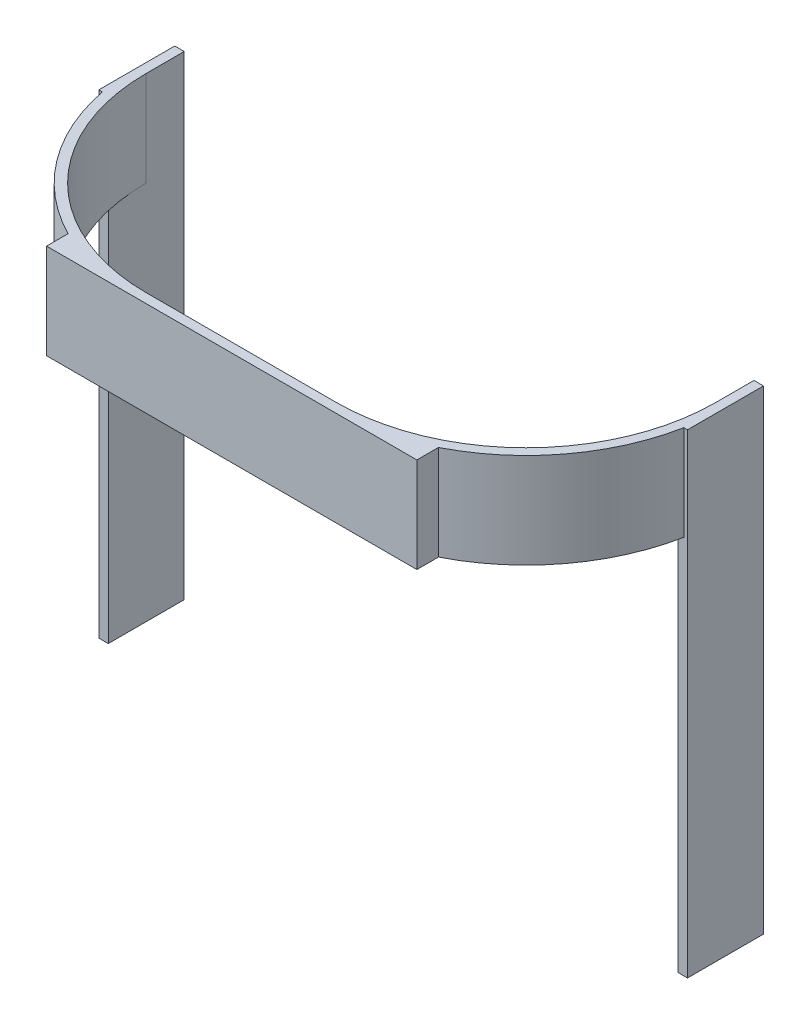
SolidWorks part; units mm, degrees
ref_plane "Front" through (0, 0, 0) normal (0, 0, 1) x (1, 0, 0)
ref_plane "Top" through (0, 0, 0) normal (0, 1, 0) x (1, 0, 0)
ref_plane "Right" through (0, 0, 0) normal (1, 0, 0) x (0, 0, -1)
sketch "草图2" plane through (0, 0, 0) normal (0, 1, 0) x (1, 0, 0)
  line L0 (-0.7345, 0) -> (19.6327, 0) construction
  line L2 (-40, -80) -> (40, -80)
  line L3 (-0.7345, 0) -> (19.6327, 0) construction
  line L5 (-40, -84) -> (40, -84)
  line L7 (-124, 16) -> (-120, 16)
  line L10 (-124, 16) -> (-124, -16)
  line L11 (-124, -16) -> (-122.4621, -16)
  line L12 (-120, 16) -> (-120, 0)
  line L13 (120, 16) -> (124, 16)
  line L14 (120, 16) -> (120, 0)
  line L15 (122.4621, -16) -> (124, -16)
  line L16 (124, 16) -> (124, -16)
  arc A0 (-120, 0) -> (-40, -80) centre (-40, 0) ccw
  arc A1 (40, -80) -> (120, 0) centre (40, 0) ccw
  arc A2 (-122.4621, -16) -> (-40, -84) centre (-40, 0) ccw
  arc A3 (40, -84) -> (122.4621, -16) centre (40, 0) ccw
  point P2 (0, 0)
  point P9 (9.4491, 0)
  dimension "D1" = 32
  dimension "D3" = 32
extrude "凸台-拉伸1" add sketch "草图2" along normal blind 40
sketch "草图3" plane through (0, 0, 0) normal (0, -1, 0) x (1, 0, 0)
  line L1 (-124, -16) -> (-120, -16)
  line L2 (-124, -16) -> (-124, 16)
  line L3 (-124, 16) -> (-120, 16)
  line L4 (-120, -16) -> (-120, 16)
  line L5 (120, -16) -> (124, -16)
  line L6 (120, -16) -> (120, 16)
  line L7 (120, 16) -> (124, 16)
  line L8 (124, -16) -> (124, 16)
extrude "凸台-拉伸2" add sketch "草图3" along normal blind 160
sketch "草图5" plane through (0, 40, 0) normal (0, 1, 0) x (1, 0, 0)
  line L0 (-40, -84) -> (-78, -84)
  line L1 (-78, -84) -> (-78, -74.9133)
  line L2 (40, -84) -> (78, -84)
  line L3 (78, -84) -> (78, -72.6077)
  line L4 (-40, -84) -> (40, -84)
  line L5 (78, -72.6077) -> (52.8973, -80.9462)
  line L6 (52.8973, -80.9462) -> (-55.5335, -80.9462)
  line L7 (-55.5335, -80.9462) -> (-78, -74.9133)
extrude "凸台-拉伸3" add sketch "草图5" against normal blind 40
